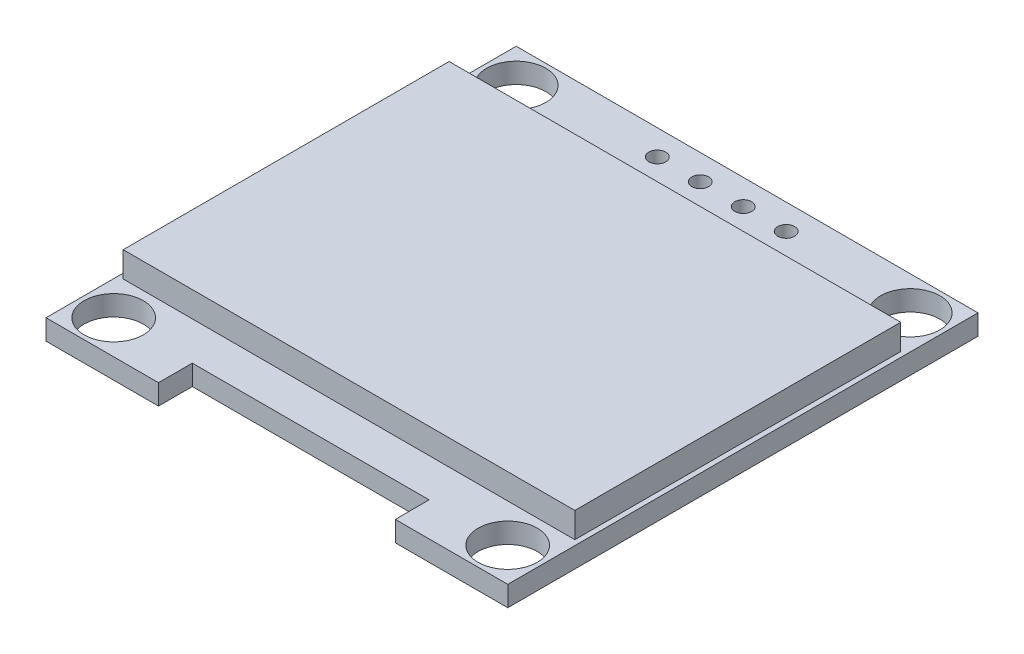
SolidWorks part; units mm, degrees
ref_plane "Plan de face" through (0, 0, 0) normal (0, 0, 1) x (1, 0, 0)
ref_plane "Plan de dessus" through (0, 0, 0) normal (0, 1, 0) x (1, 0, 0)
ref_plane "Plan de droite" through (0, 0, 0) normal (1, 0, 0) x (0, 0, -1)
sketch "Esquisse1" plane through (0, 0, 0) normal (0, 1, 0) x (1, 0, 0)
  line L0 (27.3, 0) -> (27.3, 2.0001) construction
  line L2 (0, 0) -> (0, 27.8)
  line L3 (0, 27.8) -> (27.3, 27.8)
  line L4 (27.3, 0) -> (27.3, 27.8)
  line L5 (0, 0) -> (0, 2.0001) construction
  line L6 (27.3, 2.0001) -> (0, 2.0001) construction
  line L7 (27.3, 2.0001) -> (25.2952, 2.0001) construction
  line L8 (0, 2.0001) -> (2.0027, 2.0001) construction
  line L9 (0, 27.8) -> (0, 25.8) construction
  line L10 (27.3, 27.8) -> (27.3, 25.8) construction
  line L11 (27.3, 25.8) -> (0, 25.8) construction
  line L12 (0, 25.8) -> (2, 25.8) construction
  line L13 (27.3, 25.8) -> (25.2952, 25.8) construction
  line L14 (27.3, 27.8) -> (27.3, 26.3) construction
  line L15 (0, 27.8) -> (0, 26.3) construction
  line L16 (0, 26.3) -> (27.3, 26.3) construction
  line L17 (0, 26.3) -> (9.84, 26.3) construction
  line L18 (27.3, 26.3) -> (17.46, 26.3) construction
  line L19 (9.84, 26.3) -> (12.38, 26.3) construction
  line L20 (12.38, 26.3) -> (14.92, 26.3) construction
  line L21 (0, 2.0001) -> (6.65, 2.0001) construction
  line L22 (27.3, 2.0001) -> (20.65, 2.0001) construction
  line L23 (6.65, 2.0001) -> (20.65, 2.0001)
  line L24 (6.65, 2.0001) -> (6.65, 0)
  line L25 (6.65, 0) -> (0, 0)
  line L26 (20.65, 2.0001) -> (20.65, 0)
  line L27 (20.65, 0) -> (27.3, 0)
  line L28 (2, 25.8) -> (25.2952, 2.0001) construction
  line L29 (25.2952, 25.8) -> (2.0027, 2.0001) construction
  circle A0 centre (25.2952, 2.0001) radius 1.75
  circle A1 centre (2.0027, 2.0001) radius 1.75
  circle A2 centre (25.2952, 25.8) radius 1.75
  circle A3 centre (2, 25.8) radius 1.75
  circle A4 centre (9.84, 26.3) radius 0.5
  circle A5 centre (17.46, 26.3) radius 0.5
  circle A6 centre (12.38, 26.3) radius 0.5
  circle A7 centre (14.92, 26.3) radius 0.5
extrude "Boss.-Extru.2" add sketch "Esquisse1" along normal blind 1.2
ref_plane "plan ecran" through (0, 1.2, 0) normal (0, 1, 0) x (1, 0, 0)
sketch "Esquisse9" plane through (0, 1.2, 0) normal (0, 1, 0) x (1, 0, 0)
  line L0 (2, 25.8) -> (25.2952, 2.0001) construction
  line L1 (25.2952, 25.8) -> (2.0027, 2.0001) construction
  line L3 (0.2976, 4.2661) -> (26.9976, 4.2661)
  line L4 (0.2976, 4.2661) -> (0.2976, 23.5341)
  line L5 (0.2976, 23.5341) -> (26.9976, 23.5341)
  line L6 (26.9976, 4.2661) -> (26.9976, 23.5341)
  line L7 (0.2976, 4.2661) -> (26.9976, 23.5341) construction
  line L8 (0.2976, 23.5341) -> (26.9976, 4.2661) construction
  point P8 (13.6476, 13.9001)
  dimension "D1" = 19.268
  dimension "D2" = 26.7
extrude "Boss.-Extru.3" add sketch "Esquisse9" along normal blind 1.5
sketch "Esquisse10" plane through (27.5069, 0, -25.3893) normal (0, -1, 0) x (-1, 0, 0)
  text T0 "OLED 0.96"
extrude "Enlèv. mat.-Extru.1" cut sketch "Esquisse10" against normal blind 0.5
